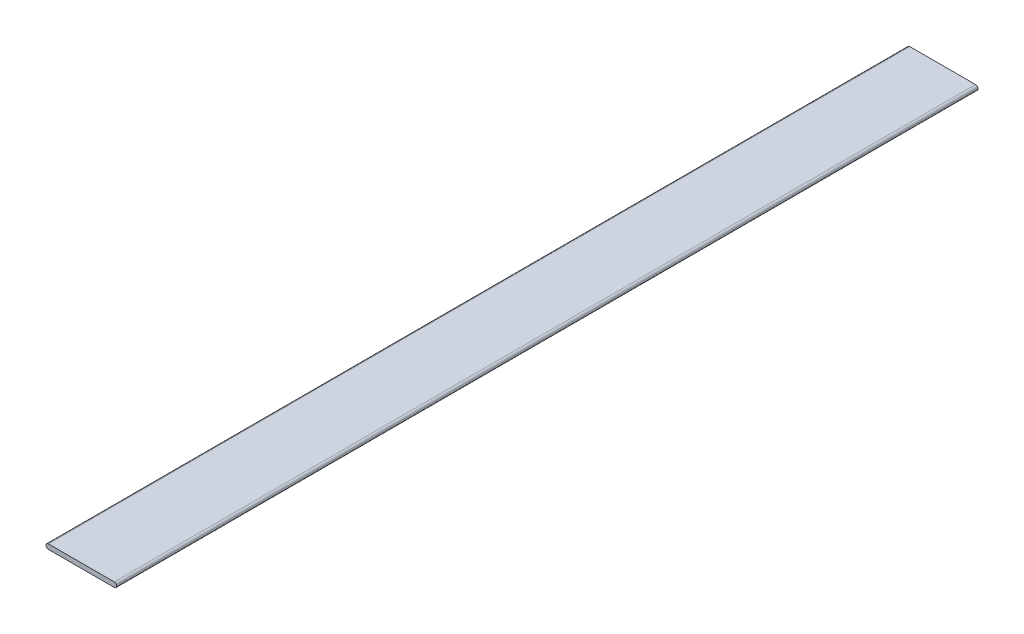
SolidWorks part; units mm, degrees
ref_plane "Front Plane" through (0, 0, 0) normal (0, 0, 1) x (1, 0, 0)
ref_plane "Top Plane" through (0, 0, 0) normal (0, 1, 0) x (1, 0, 0)
ref_plane "Right Plane" through (0, 0, 0) normal (1, 0, 0) x (0, 0, -1)
sketch "Sketch1" plane through (0, 0, 0) normal (0, 0, 1) x (1, 0, 0)
  line L0 (-5.4072, 0) -> (13.6928, 0) construction
  line L1 (-5.4072, 0.7) -> (13.6928, 0.7)
  line L2 (-5.4072, -0.7) -> (13.6928, -0.7)
  arc A0 (-5.4072, 0.7) -> (-5.4072, -0.7) centre (-5.4072, 0) ccw
  arc A1 (13.6928, -0.7) -> (13.6928, 0.7) centre (13.6928, 0) ccw
  point P3 (4.1428, 0)
extrude "Boss-Extrude1" add sketch "Sketch1" along normal blind 250
